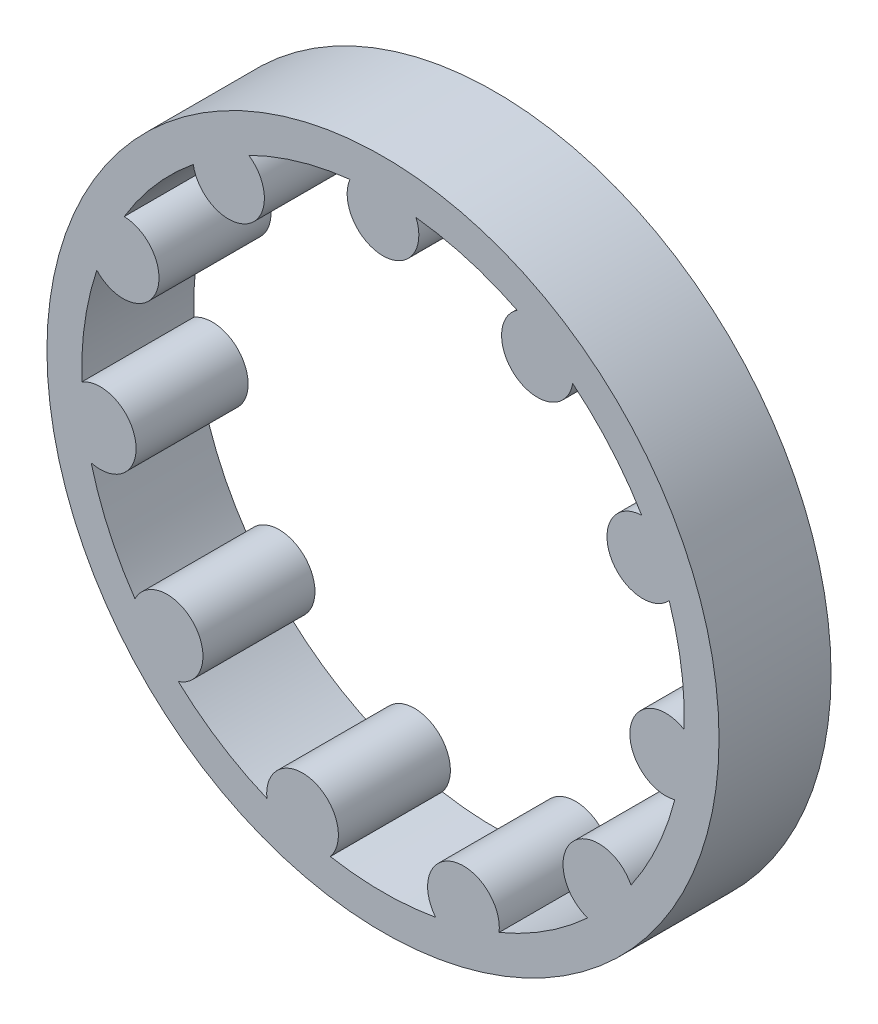
SolidWorks part; units mm, degrees
ref_plane "Front Plane" through (0, 0, 0) normal (0, 0, 1) x (1, 0, 0)
ref_plane "Top Plane" through (0, 0, 0) normal (0, 1, 0) x (1, 0, 0)
ref_plane "Right Plane" through (0, 0, 0) normal (1, 0, 0) x (0, 0, -1)
sketch "Sketch1" plane through (0, 0, 0) normal (0, 0, 1) x (1, 0, 0)
  circle A0 centre (0, 0) radius 25.5
  circle A1 centre (0, 25.5) radius 3.2
  circle A2 centre (13.7863, 21.452) radius 3.2
  circle A3 centre (23.1956, 10.5931) radius 3.2
  circle A4 centre (25.2404, -3.629) radius 3.2
  circle A5 centre (19.2716, -16.6989) radius 3.2
  circle A6 centre (7.1842, -24.4671) radius 3.2
  circle A7 centre (-7.1842, -24.4671) radius 3.2
  circle A8 centre (-19.2716, -16.6989) radius 3.2
  circle A9 centre (-25.2404, -3.629) radius 3.2
  circle A10 centre (-23.1956, 10.5931) radius 3.2
  circle A11 centre (-13.7863, 21.452) radius 3.2
  circle A12 centre (0, 0) radius 30
  circle A13 centre (0, 0) radius 26.9019
  point P28 (0, 0)
  dimension "D1" = 51
  dimension "D2" = 6.4
  dimension "D4" = 60
  dimension "D3" = 11
extrude "Boss-Extrude2" add sketch "Sketch1" along normal blind 10 contours A13 A1 | A1 A13 A0 | A0 A1 | A13 A11 | A11 A13 A0 | A0 A11 | A13 A10 | A10 A13 A0 | A0 A10 | A13 A9 | A9 A13 A0 | A0 A9 | A13 A8 | A8 A13 A0 | A0 A8 | A13 A7 | A7 A13 A0 | A0 A7 | A13 A6 | A6 A13 A0 | A0 A6 | A0 A5 | A5 A13 A0 | A13 A5 | A0 A4 | A4 A13 A0 | A13 A4 | A0 A2 | A2 A13 A0 | A13 A2 | A0 A3 | A3 A13 A0 | A13 A3 | A12 A13 A3 A4 A5 A6 A7 A8 A9 A10 A11 A1 A2
